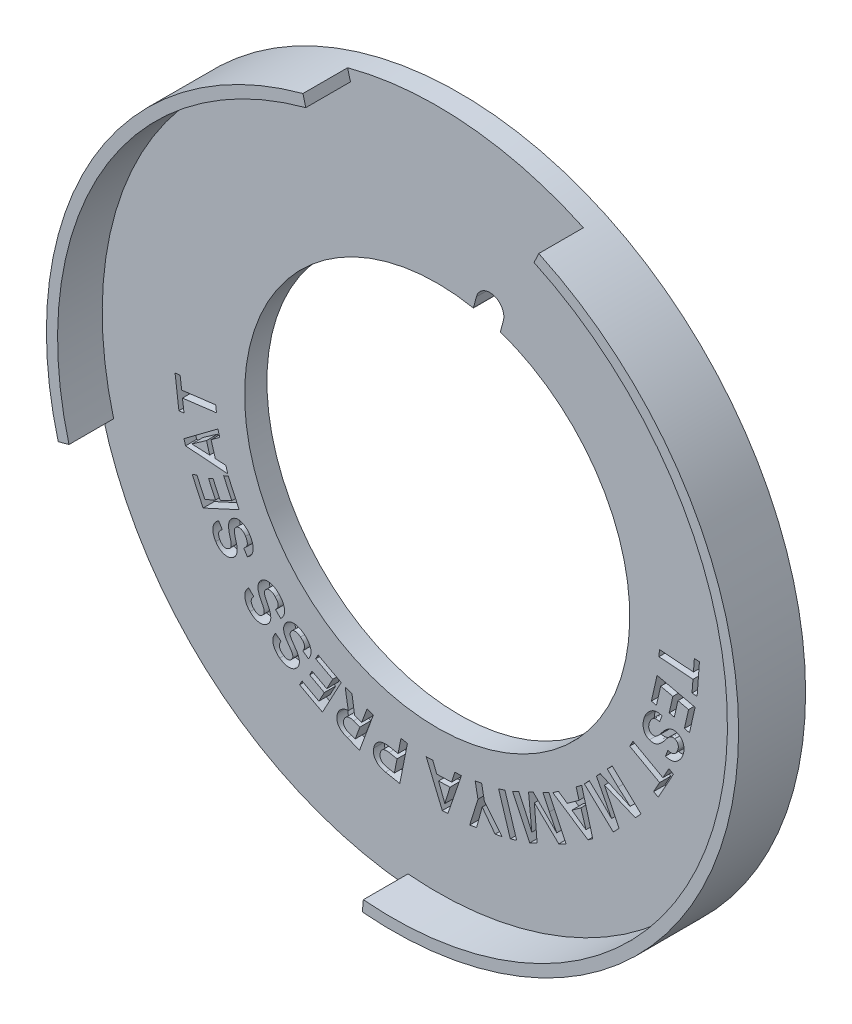
SolidWorks part; units mm, degrees
ref_plane "前视基准面" through (0, 0, 0) normal (0, 0, 1) x (1, 0, 0)
ref_plane "上视基准面" through (0, 0, 0) normal (0, 1, 0) x (1, 0, 0)
ref_plane "右视基准面" through (0, 0, 0) normal (1, 0, 0) x (0, 0, -1)
sketch "草图1" plane through (0, 0, 0) normal (0, 0, 1) x (1, 0, 0)
  circle A0 centre (0, 0) radius 17.25
  circle A1 centre (0, 0) radius 31
  dimension "D1" = 34.5
  dimension "D2" = 62
extrude "凸台-拉伸1" add sketch "草图1" along normal blind 2
sketch "草图2" plane through (0, 0, 2) normal (0, 0, 1) x (1, 0, 0)
  circle A0 centre (0, 0) radius 31 construction
  circle A1 centre (0, 0) radius 31
  circle A2 centre (0, 0) radius 30
  dimension "D1" = 1
extrude "凸台-拉伸2" add sketch "草图2" along normal blind 4
sketch "草图3" plane through (0, 0, 2) normal (0, 0, 1) x (1, 0, 0)
  line L0 (4.4646, 16.6622) -> (4.7234, 17.6281) construction
  line L1 (3.2572, 16.9857) -> (3.516, 17.9517)
  line L2 (5.672, 16.3387) -> (5.9309, 17.3046)
  line L3 (0, 17.25) -> (0, 0) construction
  circle A0 centre (0, 0) radius 17.25 construction
  arc A1 (3.2572, 16.9857) -> (5.672, 16.3387) centre (4.4646, 16.6622) ccw
  arc A2 (5.9309, 17.3046) -> (3.516, 17.9517) centre (4.7234, 17.6281) ccw
  point P4 (4.594, 17.1452)
  dimension "D1" = 2.5
  dimension "D2" = 1
  dimension "D3" = 15
extrude "切除-拉伸1" cut sketch "草图3" against normal blind 4
sketch "草图4" plane through (0, 0, 2) normal (0, 0, 1) x (1, 0, 0)
  line L0 (0, 0) -> (-8.0234, 29.9437)
  line L1 (0, 0) -> (13.1012, 28.0955)
  line L2 (5.047, 18.8356) -> (-8.0234, -29.9437) construction
  line L3 (0, 0) -> (-2.7018, -30.882)
  line L4 (0, 0) -> (-29.9437, -8.0234)
  circle A0 centre (0, 0) radius 31 construction
  arc A1 (-29.9437, -8.0234) -> (-2.7018, -30.882) centre (0, 0) ccw
  arc A2 (5.9309, 17.3046) -> (3.516, 17.9517) centre (4.7234, 17.6281) ccw construction
  arc A3 (13.1012, 28.0955) -> (-8.0234, 29.9437) centre (0, 0) ccw
  circle M13 centre (0, 0) radius 30
  dimension "D1" = 30
  dimension "D2" = 10
  dimension "D3" = 10
  dimension "D4" = 60
extrude "切除-拉伸2" cut sketch "草图4" along normal through all contours L2 L4 A1 M13 | L1 A3 L0 M13 | L2 A1 L3 M13
sketch "草图5" plane through (0, 0, 2) normal (0, 0, 1) x (1, 0, 0)
  circle A0 centre (0, 0) radius 20 construction
  text T0 "TEST MAMIYA PRESS SEAT" font "Roboto" height 3.5
  dimension "D1" = 40
extrude "切除-拉伸3" cut sketch "草图5" against normal blind 1
